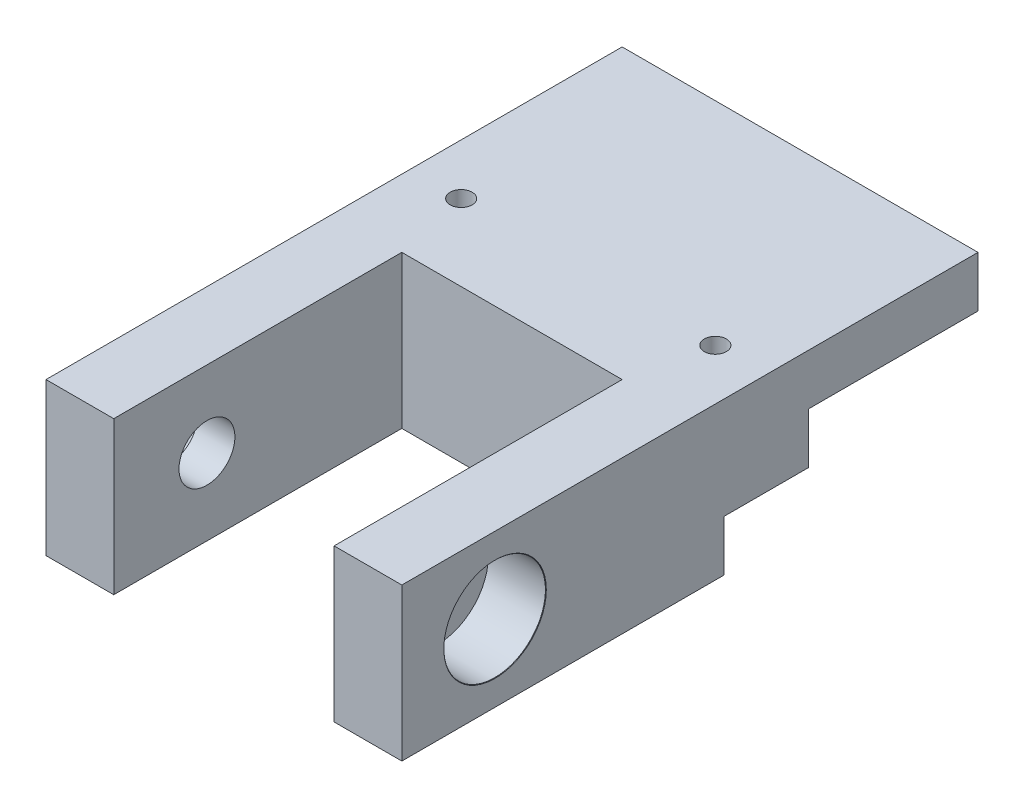
SolidWorks part; units mm, degrees
ref_plane "前视基准面" through (0, 0, 0) normal (0, 0, 1) x (1, 0, 0)
ref_plane "上视基准面" through (0, 0, 0) normal (0, 1, 0) x (1, 0, 0)
ref_plane "右视基准面" through (0, 0, 0) normal (1, 0, 0) x (0, 0, -1)
other "Configuration Table"
sketch "草图1" plane through (0, 0, 0) normal (0, 1, 0) x (1, 0, 0)
  line L1 (-10.5, 17) -> (10.5, 17)
  line L2 (-10.5, 17) -> (-10.5, -17)
  line L3 (-10.5, -17) -> (10.5, -17)
  line L4 (10.5, 17) -> (10.5, -17)
  line L5 (-10.5, 17) -> (10.5, -17) construction
  line L6 (-10.5, -17) -> (10.5, 17) construction
  point P0 (0, 0)
  dimension "D1" = 34
  dimension "D2" = 21
extrude "凸台-拉伸1" add sketch "草图1" along normal blind 9
sketch "草图4" plane through (0, 0, 0) normal (0, -1, 0) x (1, 0, 0)
  line L0 (-10.5, -7) -> (10.5, -7)
  line L1 (-10.5, -17) -> (-10.5, 17) construction
  line L2 (10.5, 17) -> (10.5, -17) construction
  line L3 (10.5, -7) -> (10.5, -17)
  line L4 (10.5, -17) -> (-10.5, -17)
  line L5 (-10.5, -17) -> (-10.5, -7)
  dimension "D1" = 10
extrude "切除-拉伸1" cut sketch "草图4" against normal blind 6
sketch "草图5" plane through (0, 0, 0) normal (0, -1, 0) x (1, 0, 0)
  line L1 (-10.5, -17) -> (10.5, -17)
  line L2 (-10.5, -17) -> (-10.5, -2)
  line L3 (-10.5, -2) -> (10.5, -2)
  line L4 (10.5, -17) -> (10.5, -2)
  line L5 (-10.5, -7) -> (-10.5, -17) construction
  line L6 (10.5, 17) -> (10.5, -7) construction
  line L7 (-10.5, -17) -> (10.5, -17) construction
  dimension "D1" = 15
extrude "切除-拉伸2" cut sketch "草图5" against normal blind 3
sketch "草图6" plane through (0, 9, 0) normal (0, 1, 0) x (1, 0, 0)
  line L1 (6.5018, 0) -> (-6.5018, 0)
  line L2 (6.5018, 0) -> (6.5018, -17)
  line L4 (-6.5018, 0) -> (-6.5018, -17)
  line L5 (-10.5, -17) -> (10.5, -17) construction
  line L8 (-6.5018, -17) -> (6.5018, -17)
  point P0 (0, -17)
  dimension "D1" = 17
extrude "切除-拉伸3" cut sketch "草图6" against normal through all
sketch "草图7" plane through (10.5, 0, 0) normal (1, 0, 0) x (0, 0, -1)
  line L0 (-17, 9) -> (-17, 0) construction
  line L1 (2, 3) -> (2, 0) construction
  point P0 (-11.5, 4.5)
  point P3 (-17, 4.5)
  dimension "D2" = 13.5
hole_wizard "M3 六角圆柱头螺钉的柱形沉头孔1" positions "草图8" profile "草图9" counterbore size "M3" standard "GB" end condition up to next
sketch "草图8" plane through (10.5, 0, 0) normal (1, 0, 0) x (0, 0, -1)
  point P0 (-11.5, 4.5)
sketch "草图9" plane through (10.5, 4.5, 11.5) normal (0, 1, 0) x (0, 0, -1)
  line L0 (0, 0) -> (0, 3.9982)
  line L1 (0, 3.9982) -> (1.7, 3.9982)
  line L3 (1.7, 3.9982) -> (1.7, 3.4)
  line L4 (3, 3.4) -> (1.7, 3.4)
  line L5 (3, 3.4) -> (3, 0.025)
  line L6 (3, 0.025) -> (3.025, 0)
  line L7 (3.025, 0) -> (0, 0)
  line L8 (-3, 0.025) -> (-3.025, 0) construction
  line L11 (0, -6.35) -> (0, 107.95) construction
  dimension "通孔孔直径" = 3.4
  dimension "通孔孔深度" = 3.9982
  dimension "柱形沉头孔直径" = 6
  dimension "柱形沉头孔深度" = 3.4
  dimension "近端锥形沉头孔直径" = 6.05
  dimension "近端锥形沉头孔角度" = 90
sketch "草图10" plane through (-10.5, 0, 0) normal (-1, 0, 0) x (0, 0, 1)
  line L0 (-2, 0) -> (17, 0) construction
  line L2 (13.1743, 1.6) -> (14.8486, 4.5)
  line L3 (14.8486, 4.5) -> (13.1743, 7.4)
  line L4 (13.1743, 7.4) -> (9.8257, 7.4)
  line L5 (9.8257, 7.4) -> (8.1514, 4.5)
  line L6 (8.1514, 4.5) -> (9.8257, 1.6)
  line L7 (9.8257, 1.6) -> (13.1743, 1.6)
  circle A0 centre (11.5, 4.5) radius 2.9 construction
  dimension "D1" = 5.8
extrude "切除-拉伸4" cut sketch "草图10" against normal blind 1.8
sketch "草图11" plane through (-8.7, 0, 0) normal (-1, 0, 0) x (0, 0, 1)
  circle A0 centre (11.5, 4.5) radius 1.65
  dimension "D1" = 3.3
extrude "切除-拉伸5" cut sketch "草图11" against normal up to next
sketch "草图12" plane through (0, 9, 0) normal (0, 1, 0) x (1, 0, 0)
  line L0 (-7.5, 4.5) -> (7.5, 4.5)
  line L1 (10.5, -17) -> (10.5, 17) construction
  line L2 (-10.5, 17) -> (-10.5, -17) construction
  line L4 (-10.5, 7) -> (10.5, 7)
  line L5 (10.5, 7) -> (10.5, 17)
  line L6 (10.5, 17) -> (-10.5, 17)
  line L7 (-10.5, 17) -> (-10.5, 7)
  line L8 (-10.5, 7) -> (10.5, 7)
  line L9 (10.5, 7) -> (10.5, 17)
  line L10 (10.5, 17) -> (-10.5, 17)
  line L11 (-10.5, 17) -> (-10.5, 7)
  dimension "D2" = 2.5
  dimension "D3" = 3
  dimension "D4" = 3
  dimension "D1" = 0
hole_wizard "孔1" positions "草图13" profile "草图14" legacy end condition up to next
sketch "草图13" plane through (0, 9, 0) normal (0, 1, 0) x (1, 0, 0)
  point P0 (-7.5, 4.5)
  point P3 (7.5, 4.5)
sketch "草图14" plane through (-7.5, 9, -4.5) normal (1, 0, 0) x (0, 0, 1)
  line L0 (0, 0) -> (0, 6)
  line L1 (0, 6) -> (0.65, 6)
  line L2 (0.65, 6) -> (0.65, 0)
  line L3 (0.65, 0) -> (0, 0)
  line L4 (0, 110) -> (0, -10) construction
  dimension "直径" = 1.3
  dimension "深度" = 6
